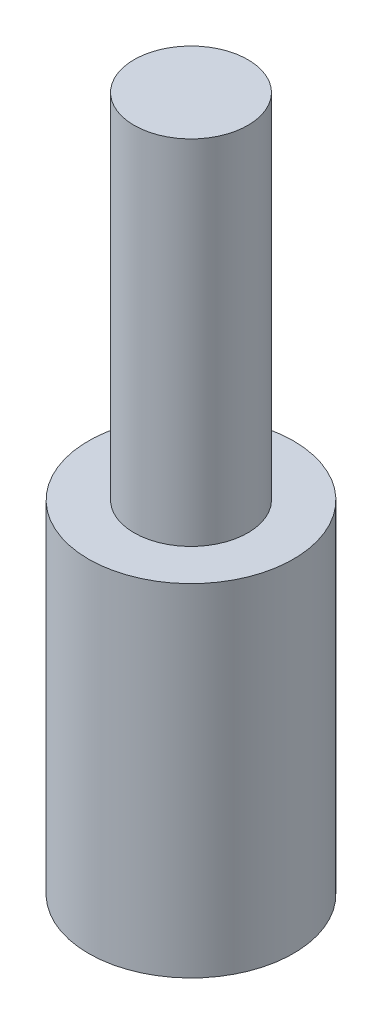
SolidWorks part; units mm, degrees
ref_plane "Front Plane" through (0, 0, 0) normal (0, 0, 1) x (1, 0, 0)
ref_plane "Top Plane" through (0, 0, 0) normal (0, 1, 0) x (1, 0, 0)
ref_plane "Right Plane" through (0, 0, 0) normal (1, 0, 0) x (0, 0, -1)
sketch "Sketch2" plane through (0, 0, 0) normal (0, 1, 0) x (1, 0, 0)
  line L0 (-4.5, 0) -> (4.5, 0) construction
  line L1 (-1.6583, 2.5) -> (1.6583, 2.5)
  line L2 (0, 4.5) -> (0, -4.5) construction
  arc A0 (-1.6583, 2.5) -> (1.6547, 2.5024) centre (0, 0) ccw
  circle A1 centre (0, 0) radius 4.5
  dimension "D1" = 2.5
  dimension "D2" = 3
  dimension "D3" = 9
extrude "Boss-Extrude1" add sketch "Sketch2" along normal blind 12
sketch "Sketch3" plane through (0, 12, 0) normal (0, 1, 0) x (1, 0, 0)
  circle A0 centre (0, 0) radius 4.5
extrude "Boss-Extrude2" add sketch "Sketch3" along normal blind 3
sketch "Sketch4" plane through (0, 15, 0) normal (0, 1, 0) x (1, 0, 0)
  circle A0 centre (0, 0) radius 2.5
extrude "Boss-Extrude3" add sketch "Sketch4" along normal blind 15.5
